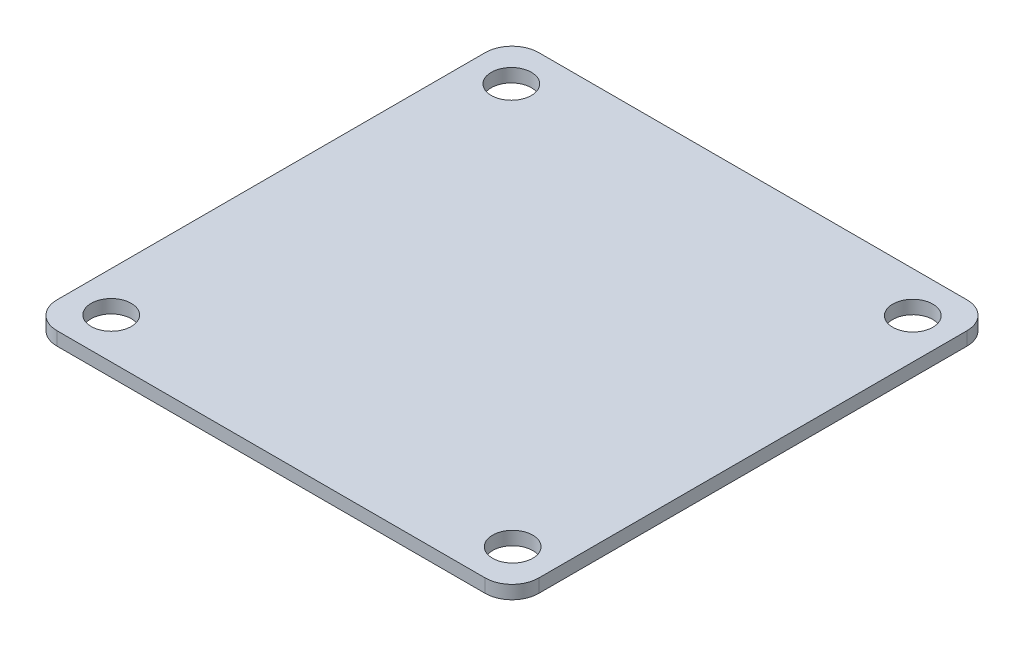
SolidWorks part; units mm, degrees
material "C-Glass Fiber"
ref_plane "Front Plane" through (0, 0, 0) normal (0, 0, 1) x (1, 0, 0)
ref_plane "Top Plane" through (0, 0, 0) normal (0, 1, 0) x (1, 0, 0)
ref_plane "Right Plane" through (0, 0, 0) normal (1, 0, 0) x (0, 0, -1)
sketch "Sketch1" plane through (0, 0, 0) normal (0, 1, 0) x (1, 0, 0)
  line L0 (3, 32.95) -> (33, 32.95) construction
  line L1 (0, 0) -> (36, 0)
  line L2 (0, 0) -> (0, 36)
  line L3 (0, 36) -> (36, 36)
  line L4 (36, 0) -> (36, 36)
  line L5 (33, 32.95) -> (33, 3.05) construction
  circle A0 centre (3, 32.95) radius 1.5
  circle A4 centre (33, 32.95) radius 1.5
  circle A5 centre (3, 3.05) radius 1.5
  circle A6 centre (33, 3.05) radius 1.5
  point P13 (18, 32.95)
  point P14 (18, 36)
  point P15 (33, 18)
  point P16 (36, 18)
  dimension "D2" = 3
  dimension "D1" = 36
  dimension "D3" = 30
  dimension "D4" = 29.9
extrude "Boss-Extrude1" add sketch "Sketch1" along normal blind 1
sketch "Sketch2" plane through (0, 0, 0) normal (0, -1, 0) x (-1, 0, 0)
  line L0 (0, 18) -> (-36, 18) construction
  line L1 (0, 36) -> (0, 0) construction
  line L2 (-36, 0) -> (-36, 36) construction
  line L3 (-36, 36) -> (0, 36) construction
  text T0 "PDB"
  dimension "D1" = 36
move or copy body "Body-Move/Copy1" bodies to move or copy 101 copy no rotation origin (0, 0.5, -18) rotation axis (1, 0, 0) rotation angle 180
fillet "Fillet1" radius 2 4 edges at (0, 0.5, -36) (0, 0.5, 0) (36, 0.5, -36) (36, 0.5, 0)
